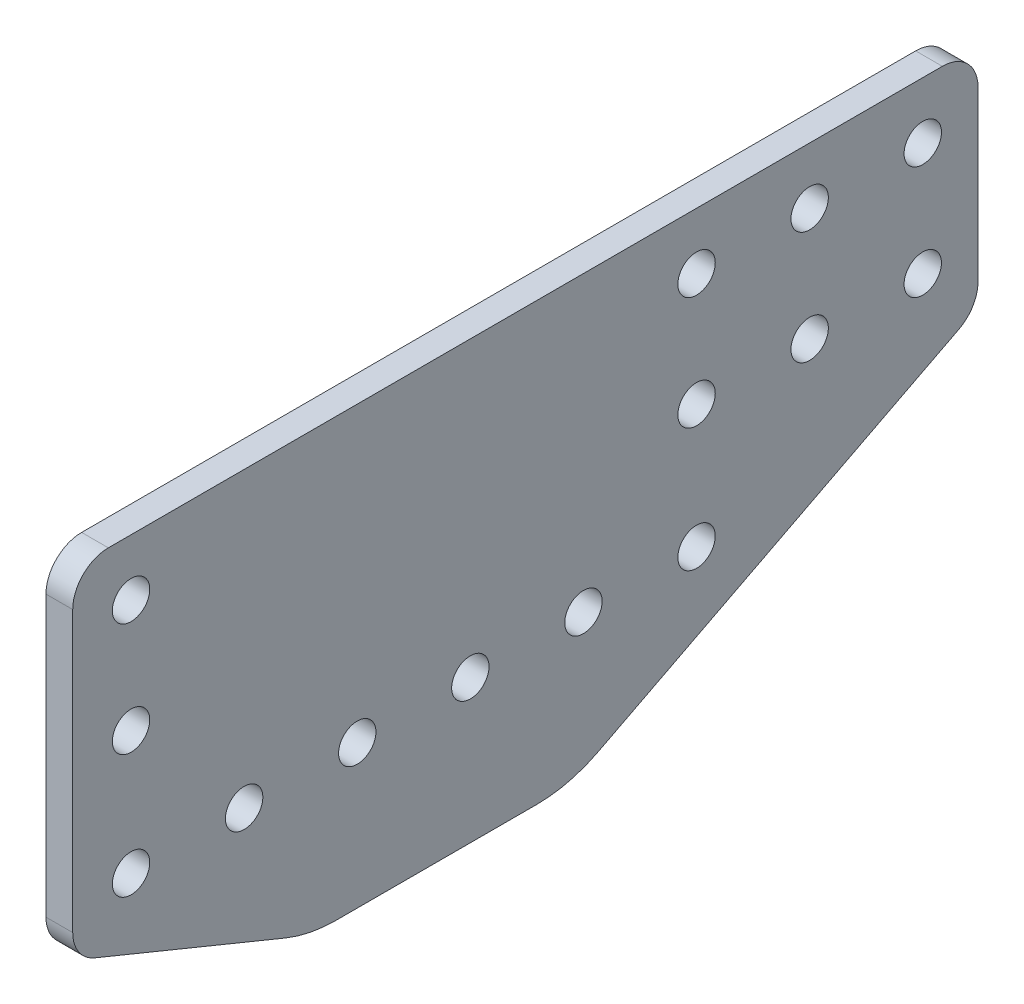
SolidWorks part; units mm, degrees
ref_plane "前视基准面" through (0, 0, 0) normal (0, 0, 1) x (1, 0, 0)
ref_plane "上视基准面" through (0, 0, 0) normal (0, 1, 0) x (1, 0, 0)
ref_plane "右视基准面" through (0, 0, 0) normal (1, 0, 0) x (0, 0, -1)
sketch "草图1" plane through (0, 0, 0) normal (1, 0, 0) x (0, 0, -1)
  line L2 (59.5296, 44.1852) -> (59.5296, 25.2262)
  line L3 (57.3587, 21.669) -> (16.8439, 0.8356)
  line L4 (9.9844, -0.8247) -> (-12.5434, -0.8247)
  line L5 (-2.9232, 48.1852) -> (55.5296, 48.1852)
  line L6 (-39.6407, 9.0677) -> (-18.2306, 0.2952)
  line L7 (-42.1241, 12.769) -> (-42.1241, 44.1852)
  line L8 (-38.1241, 48.1852) -> (-2.9232, 48.1852)
  circle A0 centre (40.626, 41.8352) radius 2.1
  arc A1 (-18.2306, 0.2952) -> (-12.5434, -0.8247) centre (-12.5434, 14.1753) ccw
  arc A2 (9.9844, -0.8247) -> (16.8439, 0.8356) centre (9.9844, 14.1753) ccw
  circle A3 centre (-35.574, 15.2668) radius 2.1
  circle A4 centre (-22.874, 15.2668) radius 2.1
  circle A5 centre (-10.174, 15.2668) radius 2.1
  circle A6 centre (2.526, 15.2668) radius 2.1
  circle A7 centre (15.226, 15.2668) radius 2.1
  circle A8 centre (27.926, 15.2668) radius 2.1
  circle A9 centre (-22.874, 15.2668) radius 2.1
  circle A10 centre (53.326, 41.8352) radius 2.1
  circle A11 centre (53.326, 29.1352) radius 2.1
  circle A12 centre (40.626, 29.1352) radius 2.1
  circle A15 centre (-35.574, 41.8352) radius 2.1
  circle A16 centre (-35.574, 29.1352) radius 2.1
  arc A17 (55.5296, 48.1852) -> (59.5296, 44.1852) centre (55.5296, 44.1852) cw
  arc A18 (59.5296, 25.2262) -> (57.3587, 21.669) centre (55.5296, 25.2262) cw
  arc A19 (-39.6407, 9.0677) -> (-42.1241, 12.769) centre (-38.1241, 12.769) cw
  arc A20 (-42.1241, 44.1852) -> (-38.1241, 48.1852) centre (-38.1241, 44.1852) cw
  circle A21 centre (27.926, 41.8352) radius 2.1
  circle A22 centre (27.926, 29.1352) radius 2.1
  circle A23 centre (40.626, 29.1352) radius 2.1
  dimension "D1" = 4
  dimension "D2" = 2
  dimension "D3" = 2
extrude "凸台-拉伸1" add sketch "草图1" along normal blind 3 contours A20 L7 A19 L6 A1 L4 A2 L3 A18 L2 A17 L5 L8 A16 A15 A12 A11 A10 A8 A7 A6 A5 A4 A3 A0
